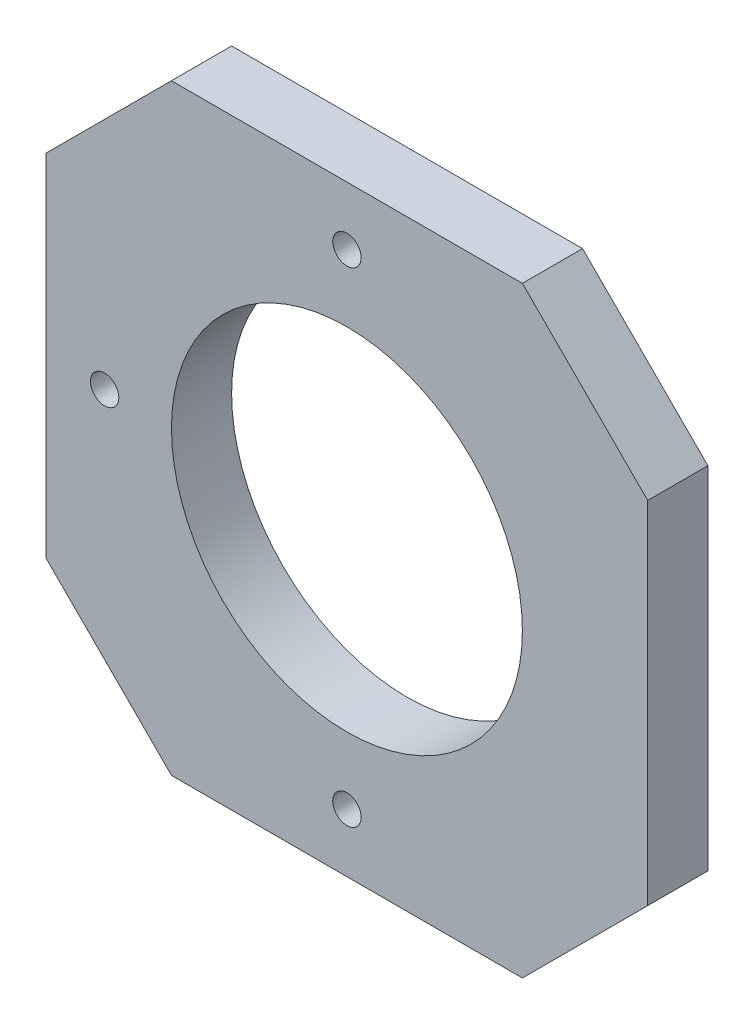
SolidWorks part; units mm, degrees
ref_plane "Спереди" through (0, 0, 0) normal (0, 0, 1) x (1, 0, 0)
ref_plane "Сверху" through (0, 0, 0) normal (0, 1, 0) x (1, 0, 0)
ref_plane "Справа" through (0, 0, 0) normal (1, 0, 0) x (0, 0, -1)
other "Configuration Table"
sketch "Эскиз1" plane through (0, 0, 0) normal (0, 0, 1) x (1, 0, 0)
  line L0 (-21, -36) -> (21, -36)
  line L1 (21, -36) -> (36, -21)
  line L2 (36, -21) -> (36, 21)
  line L3 (36, 21) -> (21, 36)
  line L4 (21, 36) -> (-21, 36)
  line L5 (-21, 36) -> (-36, 21)
  line L6 (-36, 21) -> (-36, -21)
  line L7 (-36, -21) -> (-21, -36)
  circle A0 centre (0, 0) radius 21
  circle A1 centre (0, 29) radius 1.7
  circle A2 centre (0, -29) radius 1.7
  circle A3 centre (-29, 0) radius 1.7
extrude "03_Bearing_housing_6806" add sketch "Эскиз1" along normal blind 7.2
